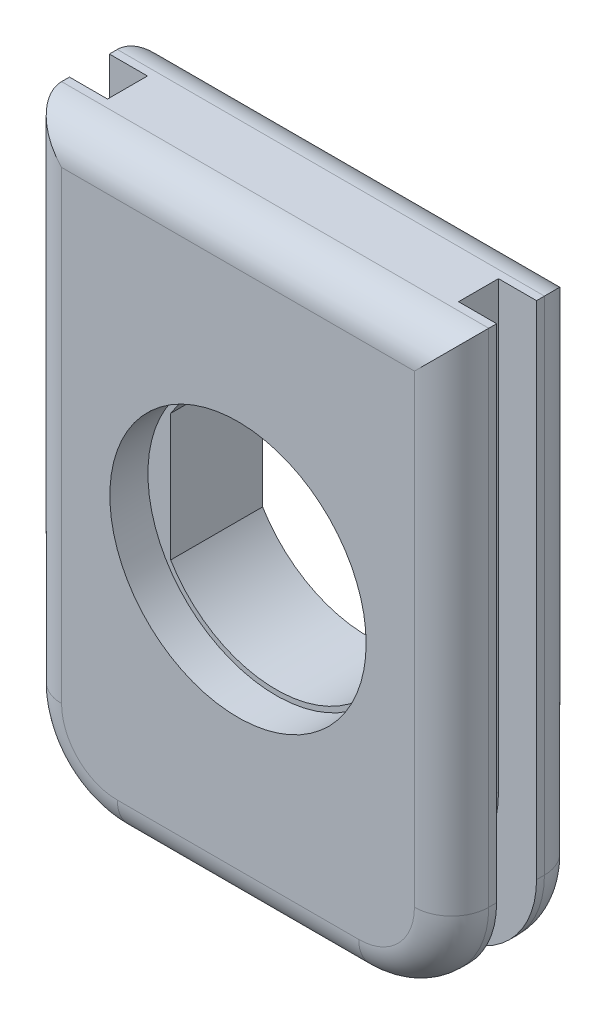
SolidWorks part; units mm, degrees
ref_plane "Front Plane" through (0, 0, 0) normal (0, 0, 1) x (1, 0, 0)
ref_plane "Top Plane" through (0, 0, 0) normal (0, 1, 0) x (1, 0, 0)
ref_plane "Right Plane" through (0, 0, 0) normal (1, 0, 0) x (0, 0, -1)
sketch "Sketch1" plane through (0, 0, 0) normal (0, 0, 1) x (1, 0, 0)
  line L1 (11.5, 16) -> (-11.5, 16)
  line L2 (11.5, 16) -> (11.5, -16)
  line L3 (11.5, -16) -> (-11.5, -16)
  line L4 (-11.5, 16) -> (-11.5, -16)
  line L5 (11.5, 16) -> (-11.5, -16) construction
  line L6 (11.5, -16) -> (-11.5, 16) construction
  point P0 (0, 0)
  dimension "D1" = 32
  dimension "D2" = 23
extrude "Boss-Extrude1" add sketch "Sketch1" along normal mid plane 7
sketch "Sketch2" plane through (0, 0, 0) normal (0, 0, 1) x (1, 0, 0)
  line L3 (-9.45, 16) -> (-11.5, 16)
  line L4 (9.45, 16) -> (11.5, 16)
  line L5 (11.5, -16) -> (11.5, 16) construction
  line L6 (9.45, -13.95) -> (9.45, 16)
  line L7 (-9.45, -13.95) -> (9.45, -13.95)
  line L8 (-9.45, 16) -> (-9.45, -13.95)
  line L9 (9.45, -13.95) -> (9.45, 16)
  line L10 (-9.45, -13.95) -> (9.45, -13.95)
  line L11 (-9.45, 16) -> (-9.45, -13.95)
  line L12 (-11.5, -16) -> (11.5, -16) construction
  line L13 (-11.5, 16) -> (-11.5, -16) construction
  line L14 (11.5, -16) -> (11.5, 16)
  line L15 (-11.5, -16) -> (11.5, -16)
  line L16 (-11.5, 16) -> (-11.5, -16)
  dimension "D1" = 2.05
extrude "Cut-Extrude1" cut sketch "Sketch2" against normal mid plane 2.15
fillet "Fillet1" radius 6 2 edges at (9.45, -13.95, 0) (-9.45, -13.95, 0)
fillet "Fillet2" radius 5 4 edges at (-11.5, -16, -2.2875) (-11.5, -16, 2.2875) (11.5, -16, 2.2875) (11.5, -16, -2.2875)
fillet "Fillet3" radius 2 12 edges at (10.0355, -14.5355, -3.5) (11.5, 2.5, -3.5) (0, 16, -3.5) (-11.5, 2.5, -3.5) (-10.0355, -14.5355, -3.5) (0, -16, -3.5) (0, 16, 3.5) (11.5, 2.5, 3.5) (10.0355, -14.5355, 3.5) (0, -16, 3.5) (-10.0355, -14.5355, 3.5) (-11.5, 2.5, 3.5)
sketch "Sketch3" plane through (0, 0, 3.5) normal (0, 0, 1) x (1, 0, 0)
  line L0 (0, 0) -> (0, 6.625) construction
  line L1 (-5.675, 3.4183) -> (-5.675, -3.4183)
  line L2 (5.675, 3.4183) -> (5.675, -3.4183)
  arc A0 (-5.675, -3.4183) -> (5.675, -3.4183) centre (0, 0) ccw
  arc A1 (5.675, 3.4183) -> (-5.675, 3.4183) centre (0, 0) ccw
  dimension "D1" = 13.25
  dimension "D2" = 11.35
extrude "Cut-Extrude2" cut sketch "Sketch3" against normal through all
sketch "Sketch5" plane through (0, 0, 3.5) normal (0, 0, 1) x (1, 0, 0)
  circle A0 centre (0, 0) radius 6.9
  dimension "D1" = 13.8
extrude "Cut-Extrude3" cut sketch "Sketch5" against normal blind 2.05
